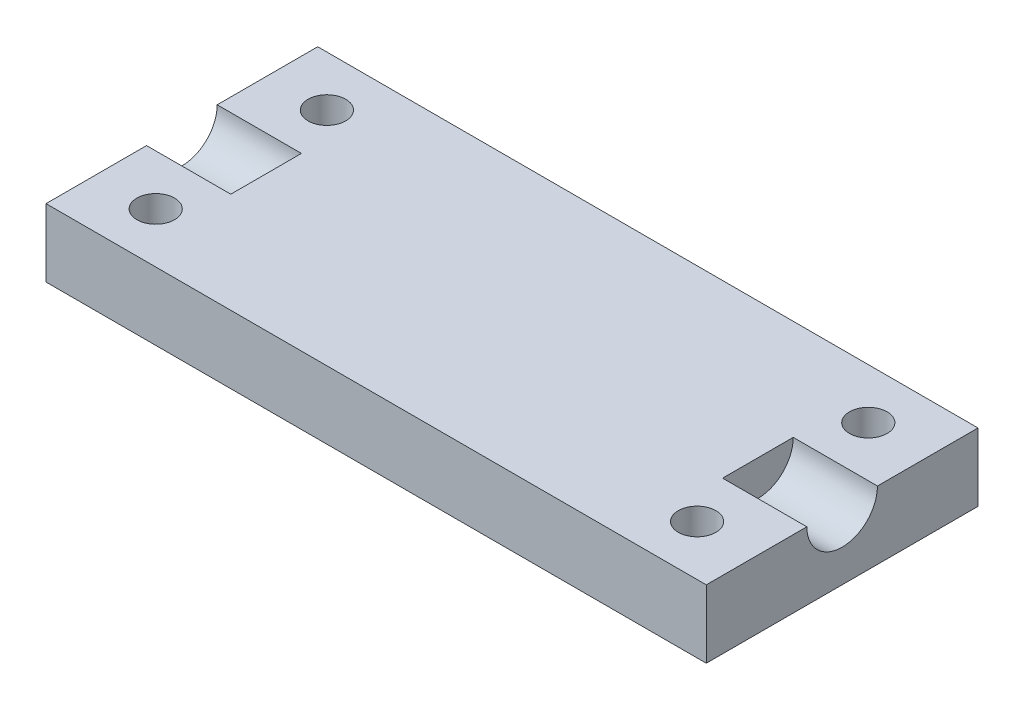
SolidWorks part; units mm, degrees
ref_plane "Front Plane" through (0, 0, 0) normal (0, 0, 1) x (1, 0, 0)
ref_plane "Top Plane" through (0, 0, 0) normal (0, 1, 0) x (1, 0, 0)
ref_plane "Right Plane" through (0, 0, 0) normal (1, 0, 0) x (0, 0, -1)
sketch "Sketch1" plane through (0, 0, 0) normal (0, 1, 0) x (1, 0, 0)
  line L1 (-30.861, -12.7) -> (30.861, -12.7)
  line L2 (-30.861, -12.7) -> (-30.861, 12.7)
  line L3 (-30.861, 12.7) -> (30.861, 12.7)
  line L4 (30.861, -12.7) -> (30.861, 12.7)
  line L5 (-30.861, -12.7) -> (30.861, 12.7) construction
  line L6 (-30.861, 12.7) -> (30.861, -12.7) construction
  point P0 (0, 0)
  dimension "D1" = 61.722
  dimension "D2" = 25.4
extrude "Boss-Extrude1" add sketch "Sketch1" against normal blind 6.35
sketch "Sketch2" plane through (30.861, 0, 0) normal (1, 0, 0) x (0, 0, -1)
  line L0 (-12.7, 0) -> (12.7, 0) construction
  circle A0 centre (0, 0) radius 3.302
  dimension "D1" = 6.604
extrude "Cut-Extrude1" cut sketch "Sketch2" against normal blind 7.874
sketch "Sketch3" plane through (-30.861, 0, 0) normal (-1, 0, 0) x (0, 0, 1)
  circle A0 centre (0, 0) radius 3.302
  dimension "D1" = 6.604
extrude "Cut-Extrude2" cut sketch "Sketch3" against normal blind 7.874
sketch "Sketch4" plane through (0, 0, 0) normal (0, 1, 0) x (1, 0, 0)
  line L0 (-30.861, -3.302) -> (-30.861, -12.7) construction
  line L1 (-30.861, 12.7) -> (-30.861, 3.302) construction
  line L2 (30.861, 3.302) -> (30.861, 12.7) construction
  line L3 (30.861, -12.7) -> (30.861, -3.302) construction
  line L6 (-30.861, 8.001) -> (30.861, 8.001) construction
  line L7 (-30.861, -8.001) -> (30.861, -8.001) construction
  circle A0 centre (25.3048, -8.001) radius 1.7589
  circle A1 centre (25.3048, 8.001) radius 1.7589
  circle A2 centre (-25.3048, 8.001) radius 1.7589
  circle A3 centre (-25.3048, -8.001) radius 1.7589
  dimension "D2" = 3.5179
  dimension "D5" = 5.5562
  dimension "D6" = 5.5562
  dimension "D7" = 5.5562
  dimension "D8" = 5.5562
extrude "Cut-Extrude11" cut sketch "Sketch4" against normal up to next
